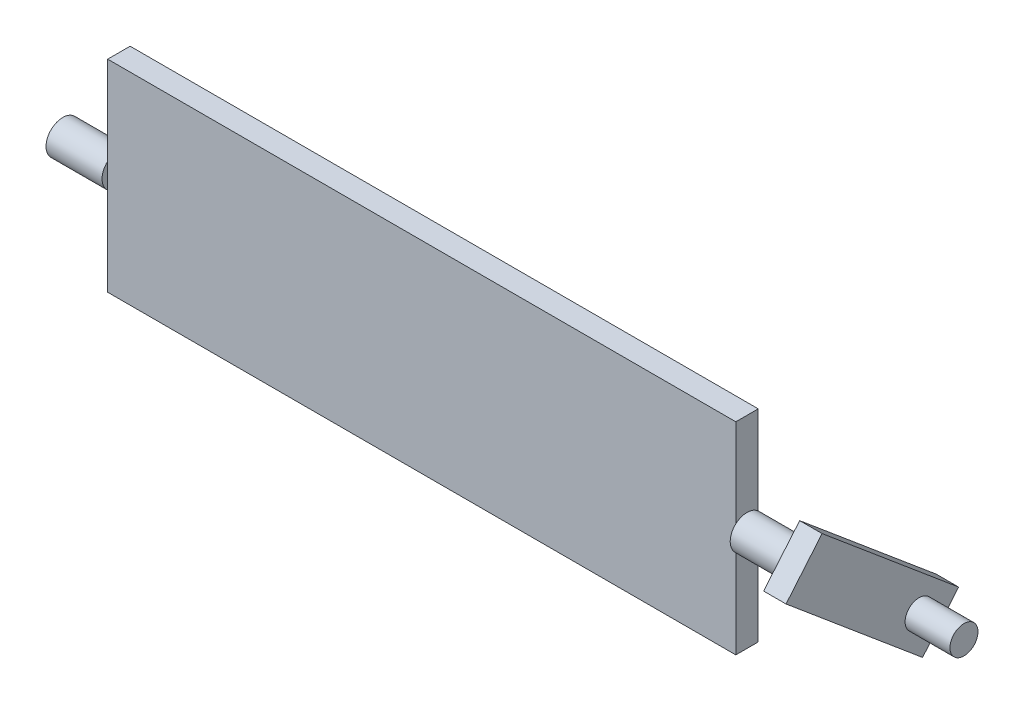
SolidWorks part; units mm, degrees
ref_plane "Front Plane" through (0, 0, 0) normal (0, 0, 1) x (1, 0, 0)
ref_plane "Top Plane" through (0, 0, 0) normal (0, 1, 0) x (1, 0, 0)
ref_plane "Right Plane" through (0, 0, 0) normal (1, 0, 0) x (0, 0, -1)
other "Configuration Table"
sketch "Sketch1" plane through (0, 0, 0) normal (0, 0, 1) x (1, 0, 0)
  line L1 (-28, -9) -> (28, -9)
  line L2 (-28, -9) -> (-28, 9)
  line L3 (-28, 9) -> (28, 9)
  line L4 (28, -9) -> (28, 9)
  line L5 (-28, -9) -> (28, 9) construction
  line L6 (-28, 9) -> (28, -9) construction
extrude "Louver_Flap" add sketch "Sketch1" along normal mid plane 2
sketch "Sketch2" plane through (-28, 0, 0) normal (-1, 0, 0) x (0, 0, 1)
  circle A0 centre (0, 0) radius 1.5
extrude "Pivot_Shaft_L" add sketch "Sketch2" along normal blind 5
sketch "Sketch3" plane through (28, 0, 0) normal (1, 0, 0) x (0, 0, -1)
  circle A0 centre (0, 0) radius 1.5
extrude "Pivot_Shaft_R" add sketch "Sketch3" along normal blind 5
sketch "Sketch4" plane through (33, 0, 0) normal (1, 0, 0) x (0, 0, -1)
  line L0 (-3.5221, -0.3081) -> (8.6504, -10.5221)
  line L1 (8.6504, -10.5221) -> (11.8644, -6.6919)
  line L2 (11.8644, -6.6919) -> (-0.3081, 3.5221)
  line L3 (-0.3081, 3.5221) -> (-3.5221, -0.3081)
extrude "Crank_Arm" add sketch "Sketch4" along normal blind 2
sketch "Sketch5" plane through (35, 0, 0) normal (1, 0, 0) x (0, 0, -1)
  circle A0 centre (8.3423, -7) radius 1.25
extrude "Crank_Pin" add sketch "Sketch5" along normal blind 4
